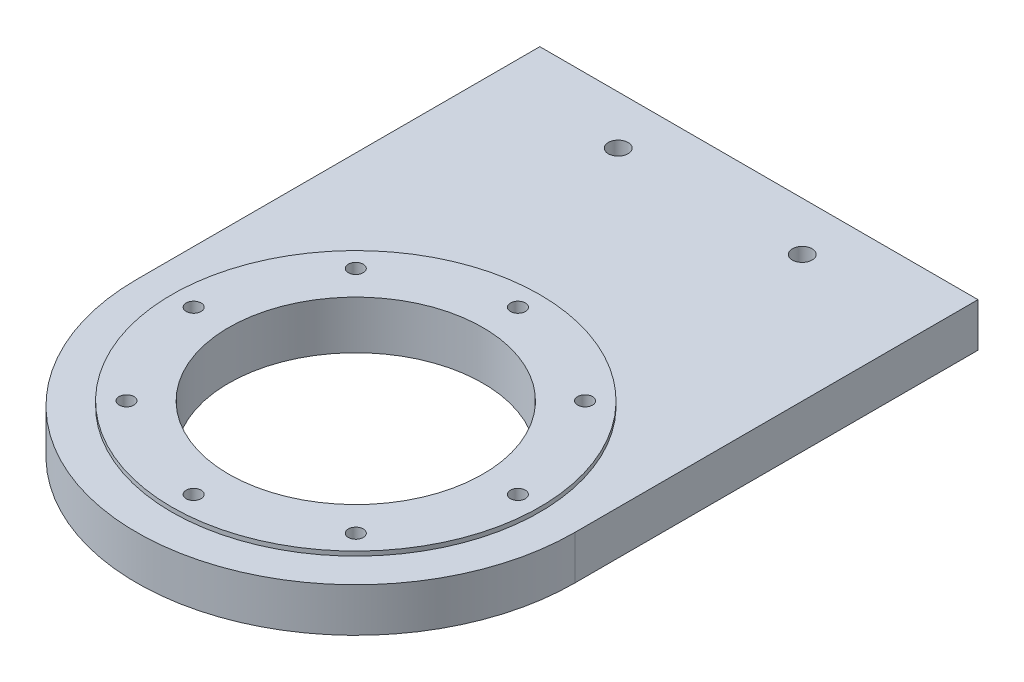
SolidWorks part; units mm, degrees
material "Aleación 6061"
ref_plane "Alzado" through (0, 0, 0) normal (0, 0, 1) x (1, 0, 0)
ref_plane "Planta" through (0, 0, 0) normal (0, 1, 0) x (1, 0, 0)
ref_plane "Vista lateral" through (0, 0, 0) normal (1, 0, 0) x (0, 0, -1)
sketch "Sk_Pared" plane through (0, 0, 0) normal (0, 1, 0) x (1, 0, 0)
  line L1 (-50, -170) -> (50, -170)
  line L2 (-50, -170) -> (-50, -78)
  line L3 (-50, -78) -> (50, -78)
  line L4 (50, -170) -> (50, -78)
  line L5 (-50, -170) -> (50, -78) construction
  line L6 (-50, -78) -> (50, -170) construction
  point P0 (0, -124)
  dimension "D1" = 100
  dimension "D2" = 92
  dimension "D3" = 124
extrude "Pared" add sketch "Sk_Pared" along normal blind 10 from offset 39.75
sketch "Sk_Cabeza" plane through (0, 0, 0) normal (0, 1, 0) x (1, 0, 0)
  circle A0 centre (0, -170) radius 50
  dimension "D1" = 100
  dimension "D2" = 170
extrude "Cabeza" add sketch "Sk_Cabeza" along normal blind 10 from offset 39.75
sketch "Sk_Asiento_1mm" plane through (0, 0, 0) normal (0, 1, 0) x (1, 0, 0)
  circle A0 centre (0, -170) radius 42
  circle A1 centre (0, -170) radius 29
  dimension "D1" = 84
  dimension "D3" = 58
  dimension "D2" = 170
  dimension "D4" = 170
extrude "Asiento_1mm" add sketch "Sk_Asiento_1mm" along normal blind 1 from offset 29.75
sketch "Sk_Paso_boss_J2" plane through (0, 0, 0) normal (0, 1, 0) x (1, 0, 0)
  circle A0 centre (0, -170) radius 29
  dimension "D1" = 58
  dimension "D2" = 170
extrude "Paso_boss_J2" cut sketch "Sk_Paso_boss_J2" along normal blind 11 from offset 39.75
sketch "Sk_Pasantes_M3_estator_J2" plane through (0, 0, 0) normal (0, 1, 0) x (1, 0, 0)
  circle A0 centre (37, -170) radius 1.7
  circle A1 centre (26.163, -196.163) radius 1.7
  circle A2 centre (0, -207) radius 1.7
  circle A3 centre (-26.163, -196.163) radius 1.7
  circle A4 centre (-37, -170) radius 1.7
  circle A5 centre (-26.163, -143.837) radius 1.7
  circle A6 centre (0, -133) radius 1.7
  circle A7 centre (26.163, -143.837) radius 1.7
  dimension "D1" = 3.4
  dimension "D4" = 3.4
  dimension "D7" = 3.4
  dimension "D9" = 3.4
  dimension "D12" = 3.4
  dimension "D15" = 3.4
  dimension "D18" = 3.4
  dimension "D20" = 3.4
  dimension "D2" = 37
  dimension "D3" = 170
  dimension "D5" = 26.163
  dimension "D6" = 196.163
  dimension "D8" = 207
  dimension "D10" = 26.163
  dimension "D11" = 196.163
  dimension "D13" = 37
  dimension "D14" = 170
  dimension "D16" = 26.163
  dimension "D17" = 143.837
  dimension "D19" = 133
  dimension "D21" = 26.163
  dimension "D22" = 143.837
extrude "Pasantes_M3_estator_J2" cut sketch "Sk_Pasantes_M3_estator_J2" along normal blind 11 from offset 39.75
sketch "Sk_Pasantes_M4_angulos" plane through (0, 0, 0) normal (0, 1, 0) x (1, 0, 0)
  circle A0 centre (-21, -89.11) radius 2.25
  circle A1 centre (21, -89.11) radius 2.25
  dimension "D1" = 4.5
  dimension "D4" = 4.5
  dimension "D2" = 21
  dimension "D3" = 89.11
  dimension "D5" = 21
  dimension "D6" = 89.11
extrude "Pasantes_M4_angulos" cut sketch "Sk_Pasantes_M4_angulos" along normal blind 10 from offset 39.75
